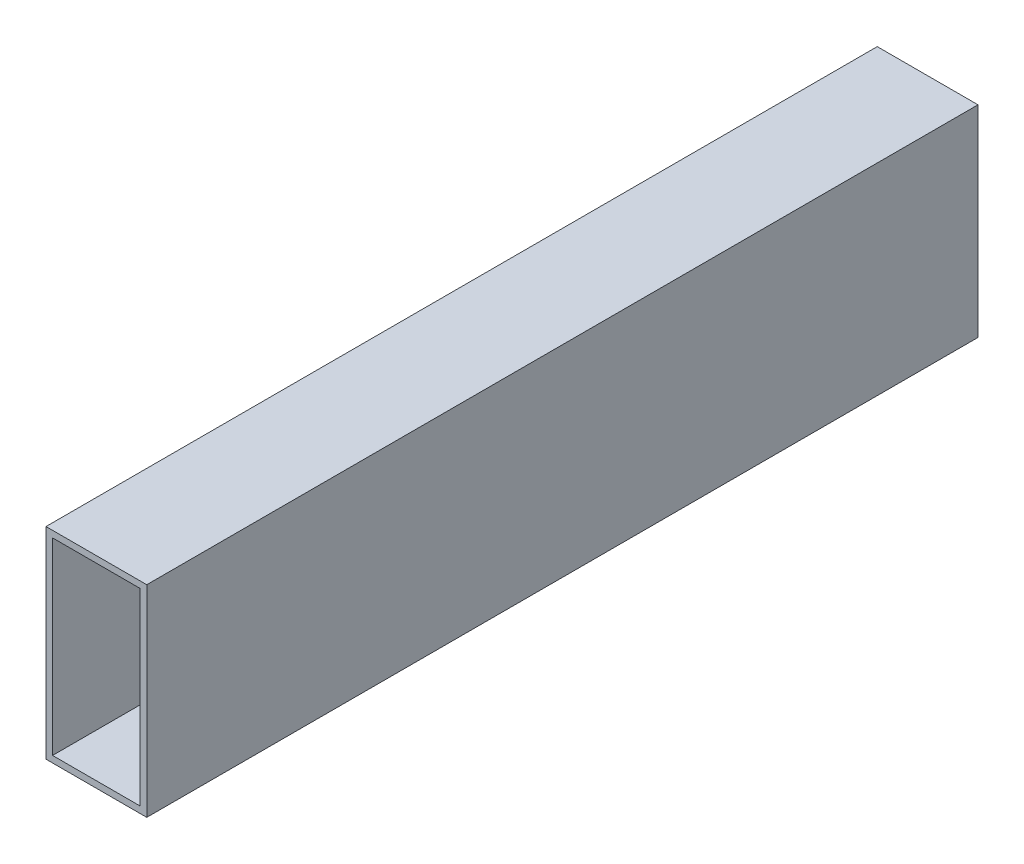
SolidWorks part; units mm, degrees
ref_plane "Front Plane" through (0, 0, 0) normal (0, 0, 1) x (1, 0, 0)
ref_plane "Top Plane" through (0, 0, 0) normal (0, 1, 0) x (1, 0, 0)
ref_plane "Right Plane" through (0, 0, 0) normal (1, 0, 0) x (0, 0, -1)
sketch "Sketch1" plane through (0, 0, 0) normal (0, 0, 1) x (1, 0, 0)
  line L1 (-50.4994, -42.8662) -> (-25.0994, -42.8662)
  line L2 (-50.4994, -42.8662) -> (-50.4994, 7.9338)
  line L3 (-50.4994, 7.9338) -> (-25.0994, 7.9338)
  line L4 (-25.0994, -42.8662) -> (-25.0994, 7.9338)
  line L5 (-48.8484, 6.2828) -> (-26.7504, 6.2828)
  line L6 (-48.8484, 6.2828) -> (-48.8484, -41.2152)
  line L7 (-48.8484, -41.2152) -> (-26.7504, -41.2152)
  line L8 (-26.7504, 6.2828) -> (-26.7504, -41.2152)
  line L9 (-48.8484, 6.2828) -> (-26.7504, -41.2152) construction
  line L10 (-48.8484, -41.2152) -> (-26.7504, 6.2828) construction
  point P4 (-37.7994, -17.4662)
  dimension "D1" = 25.4
  dimension "D2" = 50.8
  dimension "D3" = 1.651
  dimension "D4" = 1.651
  dimension "D5" = 1.651
  dimension "D6" = 1.651
extrude "Boss-Extrude1" add sketch "Sketch1" along normal blind 209.55
